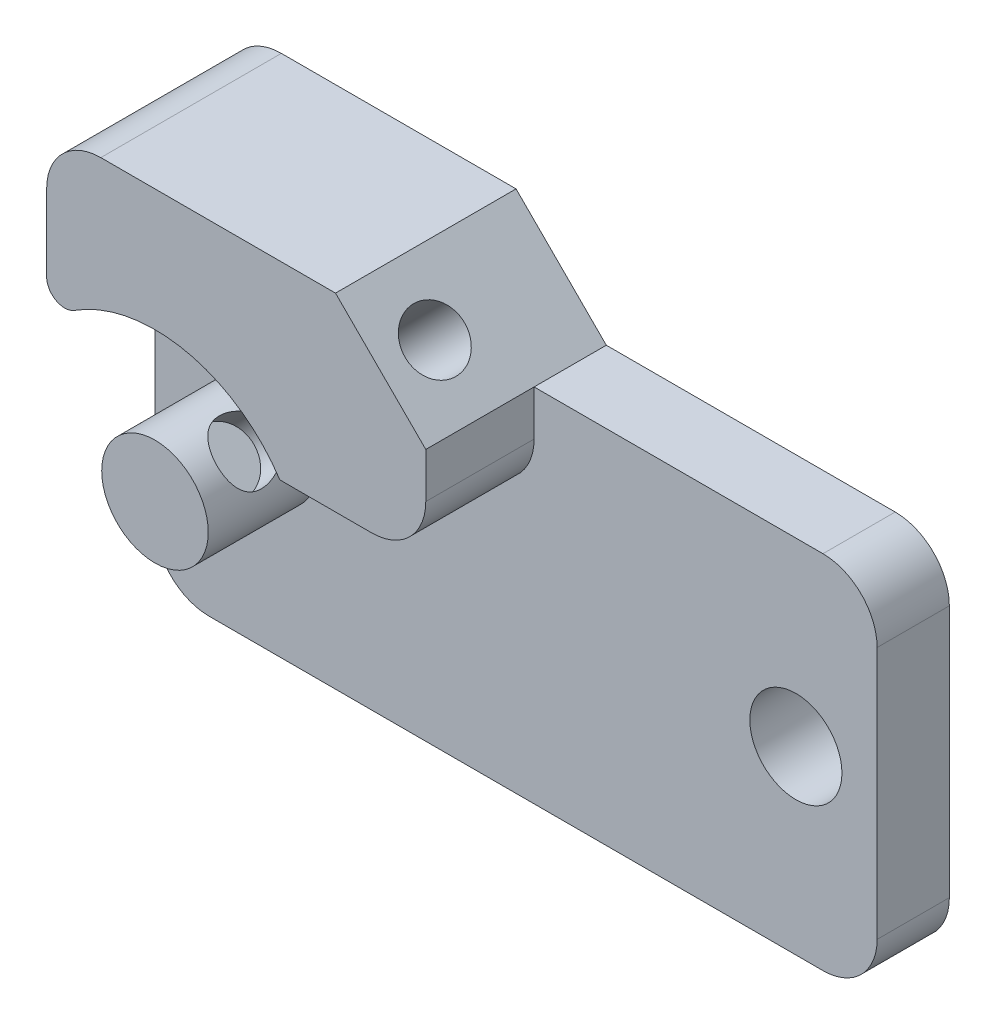
SolidWorks part; units mm, degrees
ref_plane "Plan de face" through (0, 0, 0) normal (0, 0, 1) x (1, 0, 0)
ref_plane "Plan de dessus" through (0, 0, 0) normal (0, 1, 0) x (1, 0, 0)
ref_plane "Plan de droite" through (0, 0, 0) normal (1, 0, 0) x (0, 0, -1)
sketch "Esquisse1" plane through (0, 0, 0) normal (0, 0, 1) x (1, 0, 0)
  line L1 (0, 0) -> (40, 0)
  line L2 (0, 0) -> (0, 20)
  line L3 (0, 20) -> (40, 20)
  line L4 (40, 0) -> (40, 20)
  dimension "D1" = 20
  dimension "D2" = 40
extrude "Boss.-Extru.1" add sketch "Esquisse1" along normal blind 4
sketch "Esquisse2" plane through (0, 0, 4) normal (0, 0, 1) x (1, 0, 0)
  line L0 (0, 10) -> (6, 10) construction
  line L1 (0, 20) -> (0, 0) construction
  circle A0 centre (6, 10) radius 2.95
  dimension "D1" = 5.9
  dimension "D2" = 6
extrude "Boss.-Extru.2" add sketch "Esquisse2" along normal blind 6
sketch "Esquisse3" plane through (0, 0, 4) normal (0, 0, 1) x (1, 0, 0)
  line L0 (6, 10) -> (35.5, 10) construction
  circle A0 centre (35.5, 10) radius 2.55
  dimension "D1" = 5.1
  dimension "D2" = 29.5
extrude "Enlèv. mat.-Extru.1" cut sketch "Esquisse3" against normal through all both and the other way through all
sketch "Esquisse4" plane through (0, 0, 4) normal (0, 0, 1) x (1, 0, 0)
  line L0 (21, 20) -> (21, 25)
  line L1 (40, 20) -> (0, 20) construction
  line L2 (21, 25) -> (0, 25)
  line L3 (0, 25) -> (0, 20)
  line L4 (21, 20) -> (0, 20)
  dimension "D1" = 21
  dimension "D2" = 5
extrude "Boss.-Extru.4" add sketch "Esquisse4" against normal up to vertex (4 mm away) up to point (40, 20, 0)
sketch "Esquisse5" plane through (0, 0, 4) normal (0, 0, 1) x (1, 0, 0)
  line L0 (0, 25) -> (21, 25)
  line L1 (21, 25) -> (21, 14.5)
  line L2 (21, 14.5) -> (0, 14.5)
  line L3 (0, 25) -> (0, 0) construction
  line L4 (0, 14.5) -> (0, 25)
  dimension "D1" = 10.5
extrude "Boss.-Extru.5" add sketch "Esquisse5" along normal blind 6
sketch "Esquisse6" plane through (0, 0, 10) normal (0, 0, 1) x (1, 0, 0)
  circle A0 centre (6, 10) radius 8.25
  circle A1 centre (6, 10) radius 2.95
  circle A2 centre (6, 10) radius 2.95 construction
  dimension "D1" = 16.5
extrude "Enlèv. mat.-Extru.2" cut sketch "Esquisse6" against normal up to vertex (6 mm away)
chamfer "Chanfrein1" distance 5 angle 45 1 edges at (21, 25, 5)
sketch "Esquisse7" plane through (20.5, 20.5, 0) normal (0.7071, 0.7071, 0) x (0, 0, -1)
  line L0 (-10, 2.8284) -> (-7, 2.8284) construction
  line L1 (-10, -0.7071) -> (-10, 6.364) construction
  circle A0 centre (-7, 2.8284) radius 1.65
  dimension "D1" = 3.3
  dimension "D2" = 3
extrude "Enlèv. mat.-Extru.3" cut sketch "Esquisse7" against normal blind 16.5
fillet "Congé1" radius 3 5 edges at (0, 25, 5) (21, 14.5, 7) (40, 20, 2) (40, 0, 2) (0, 0, 2)
fillet "Congé2" radius 1 1 edges at (0, 15.6624, 7)
